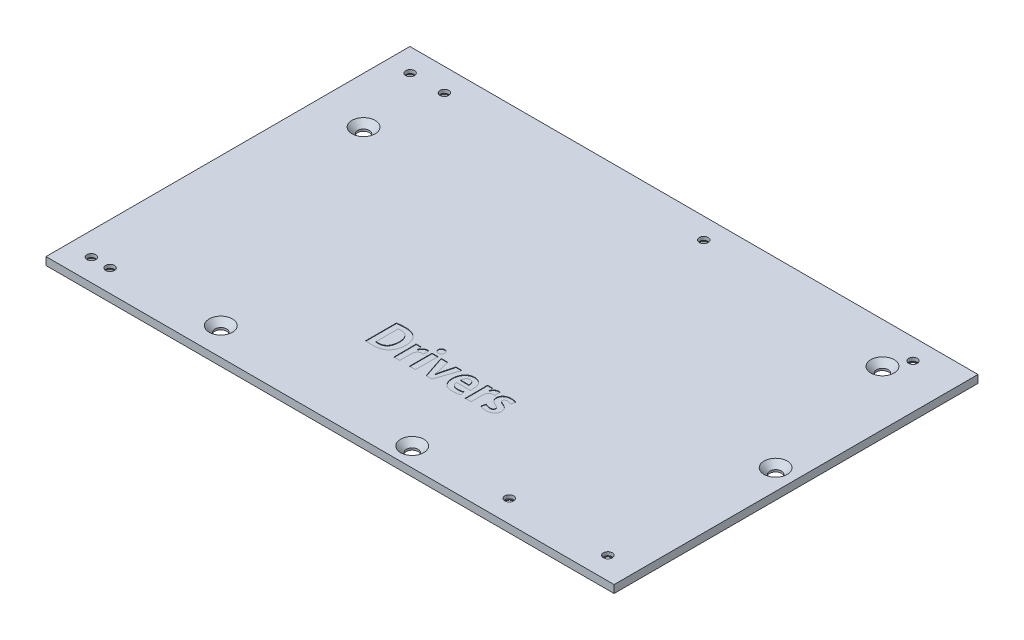
SolidWorks part; units mm, degrees
ref_plane "Alzado" through (0, 0, 0) normal (0, 0, 1) x (1, 0, 0)
ref_plane "Planta" through (0, 0, 0) normal (0, 1, 0) x (1, 0, 0)
ref_plane "Vista lateral" through (0, 0, 0) normal (1, 0, 0) x (0, 0, -1)
sketch "Sketch1" plane through (0, 0, 0) normal (0, 1, 0) x (1, 0, 0)
  line L1 (-104.4575, -65.119) -> (104.4575, -65.119)
  line L2 (-104.4575, -65.119) -> (-104.4575, 65.119)
  line L3 (-104.4575, 65.119) -> (104.4575, 65.119)
  line L4 (104.4575, -65.119) -> (104.4575, 65.119)
  line L5 (-104.4575, -65.119) -> (104.4575, 65.119) construction
  line L6 (-104.4575, 65.119) -> (104.4575, -65.119) construction
  circle A0 centre (-100.5175, 61.251) radius 1.5
  circle A1 centre (-87.3095, 61.251) radius 1.5
  circle A2 centre (92.3925, 62.141) radius 1.5
  circle A3 centre (11.7475, 62.141) radius 1.5
  circle A4 centre (60.4925, -61.559) radius 1.5
  circle A5 centre (98.4925, -61.559) radius 1.5
  circle A6 centre (-93.3165, -61.559) radius 1.5
  circle A7 centre (-100.5175, -61.559) radius 1.5
  point P0 (0, 0)
  dimension "D3" = 3.94
  dimension "D5" = 3
  dimension "D1" = 130.238
  dimension "D2" = 208.915
  dimension "D4" = 3.56
  dimension "D6" = 199.01
  dimension "D7" = 123.7
  dimension "D8" = 6.1
  dimension "D9" = 122.81
  dimension "D10" = 192.91
  dimension "D11" = 38
  dimension "D12" = 153.809
  dimension "D13" = 80.645
  dimension "D14" = 13.208
sketch "Sketch2" plane through (0, 0, 0) normal (0, 1, 0) x (1, 0, 0)
  line L16 (-109.4575, -70.119) -> (109.4575, -70.119)
  line L17 (-109.4575, 70.119) -> (-109.4575, -70.119)
  line L18 (109.4575, 70.119) -> (-109.4575, 70.119)
  line L19 (109.4575, -70.119) -> (109.4575, 70.119)
  line L20 (-109.4575, -70.119) -> (109.4575, -70.119)
  line L21 (-109.4575, 70.119) -> (-109.4575, -70.119)
  line L22 (109.4575, 70.119) -> (-109.4575, 70.119)
  line L23 (109.4575, -70.119) -> (109.4575, 70.119)
  circle A0 centre (-100.5175, -61.559) radius 1.5 construction
  circle A1 centre (-93.3165, -61.559) radius 1.5 construction
  circle A2 centre (98.4925, -61.559) radius 1.5 construction
  circle A3 centre (60.4925, -61.559) radius 1.5 construction
  circle A4 centre (92.3925, 62.141) radius 1.5 construction
  circle A5 centre (11.7475, 62.141) radius 1.5 construction
  circle A6 centre (-100.5175, 61.251) radius 1.5 construction
  circle A7 centre (-87.3095, 61.251) radius 1.5 construction
  circle A8 centre (-87.3095, 61.251) radius 1.5
  circle A9 centre (-100.5175, 61.251) radius 1.5
  circle A10 centre (11.7475, 62.141) radius 1.5
  circle A11 centre (92.3925, 62.141) radius 1.5
  circle A12 centre (60.4925, -61.559) radius 1.5
  circle A13 centre (98.4925, -61.559) radius 1.5
  circle A14 centre (-93.3165, -61.559) radius 1.5
  circle A15 centre (-100.5175, -61.559) radius 1.5
  dimension "D1" = 5
extrude "Boss-Extrude1" add sketch "Sketch2" along normal blind 3
sketch "Sketch3" plane through (0, 3, 0) normal (0, 1, 0) x (1, 0, 0)
  line L0 (-20.9409, -36.6466) -> (64.3186, -36.6466) construction
  line L1 (-104.4575, 65.119) -> (104.4575, -65.119) construction
  text T0 "Drivers" font "Adobe Gothic Std B" height 12
extrude "Cut-Extrude2" cut sketch "Sketch3" against normal blind 0.2
sketch "Sketch4" plane through (0, 3, 0) normal (0, 1, 0) x (1, 0, 0)
  line L4 (-104.4575, -65.119) -> (104.4575, -65.119)
  line L5 (104.4575, -65.119) -> (104.4575, 65.119)
  line L6 (104.4575, 65.119) -> (-104.4575, 65.119)
  line L7 (-104.4575, 65.119) -> (-104.4575, -65.119)
  line L8 (-104.4575, -65.119) -> (104.4575, -65.119)
  line L9 (104.4575, -65.119) -> (104.4575, 65.119)
  line L10 (104.4575, 65.119) -> (-104.4575, 65.119)
  line L11 (-104.4575, 65.119) -> (-104.4575, -65.119)
  circle A1 centre (60.4925, -61.559) radius 1.5
  circle A2 centre (60.4925, -61.559) radius 1.5
  circle A3 centre (11.7475, 62.141) radius 1.5
  circle A4 centre (11.7475, 62.141) radius 1.5
  circle A5 centre (92.3925, 62.141) radius 1.5
  circle A6 centre (92.3925, 62.141) radius 1.5
  circle A7 centre (-87.3095, 61.251) radius 1.5
  circle A8 centre (-87.3095, 61.251) radius 1.5
  circle A9 centre (-100.5175, 61.251) radius 1.5
  circle A10 centre (-100.5175, 61.251) radius 1.5
  circle A11 centre (-100.5175, -61.559) radius 1.5
  circle A12 centre (-100.5175, -61.559) radius 1.5
  circle A13 centre (-93.3165, -61.559) radius 1.5
  circle A14 centre (-93.3165, -61.559) radius 1.5
  circle A15 centre (98.4925, -61.559) radius 1.5
  circle A16 centre (98.4925, -61.559) radius 1.5
  dimension "D1" = 0
  dimension "D2" = 0
  dimension "D3" = 0
  dimension "D4" = 0
  dimension "D5" = 0
  dimension "D6" = 0
  dimension "D7" = 0
  dimension "D8" = 0
  dimension "D9" = 0
extrude "Boss-Extrude2" [suppressed] add sketch "Sketch4" along normal blind 2
sketch "Sketch5" plane through (0, 0, 0) normal (0, -1, 0) x (1, 0, 0)
  line L0 (-62.546, 67.4022) -> (124.1921, -83.3589) construction
  line L1 (-109.4575, -70.119) -> (-109.4575, 70.119) construction
  line L2 (109.4575, 70.119) -> (109.4575, -70.119) construction
  line L3 (109.4575, -70.119) -> (-109.4575, -70.119) construction
  line L4 (-109.4575, 70.119) -> (109.4575, 70.119) construction
  line L5 (0.2472, 42.6075) -> (-61.066, -8.7802) construction
  line L6 (-109.4575, -49.3381) -> (33.0725, 70.119) construction
  circle A0 centre (-52.7309, 59.478) radius 2.4699
  circle A1 centre (-91.4772, -34.2685) radius 2.1023
  circle A2 centre (88.3441, -54.4174) radius 2.6744
  circle A3 centre (24.3004, 62.767) radius 2.289
  circle A4 centre (101.6013, 0) radius 2.0628
  point P18 (-30.4094, 16.9136)
  dimension "D1" = 46.9115
  dimension "D2" = 14.7346
  dimension "D3" = 13.2399
  dimension "D4" = 2.7168
  dimension "D5" = 61.3388
  dimension "D6" = 48.3915
  dimension "D7" = 27.5115
  dimension "D8" = 109.7047
hole_wizard "CSK for M4 Hex Socket Countersunk Cap Screw1" positions "Sketch6" profile "Sketch7" countersink size "M4" standard "ISO" end condition through all
sketch "Sketch6" plane through (0, 3, 0) normal (0, 1, 0) x (1, 0, 0)
  point P0 (-52.7309, -59.478)
  point P3 (24.3004, -62.767)
  point P6 (-91.4772, 34.2685)
  point P9 (88.3441, 54.4174)
  point P12 (101.6013, 0)
sketch "Sketch7" plane through (-52.7309, 3, 59.478) normal (1, 0, 0) x (0, 0, 1)
  line L0 (0, 0) -> (0, 3)
  line L1 (0, 3) -> (2.25, 3)
  line L2 (2.25, 3) -> (2.25, 2.23)
  line L3 (2.25, 2.23) -> (4.48, 0)
  line L5 (4.48, 0) -> (0, 0)
  line L6 (-2.25, 2.23) -> (-4.48, 0) construction
  line L11 (0, -6.35) -> (0, 107.95) construction
  dimension "Thru Hole Dia." = 4.5
  dimension "Thru Hole Depth" = 3
  dimension "Near C'Sink Dia." = 8.96
  dimension "Near C'Sink Angle" = 90
sketch "Sketch8" [suppressed] plane through (0, 3, 0) normal (0, 1, 0) x (1, 0, 0)
  circle A0 centre (-91.4772, 34.2685) radius 1
  circle A1 centre (-52.7309, -59.478) radius 1
  circle A2 centre (24.3004, -62.767) radius 1
  circle A3 centre (88.3441, 54.4174) radius 1
  circle A4 centre (101.6013, 0) radius 1
  dimension "D1" = 2
extrude "Cut-Extrude3" [suppressed] cut sketch "Sketch8" against normal through all
sketch "Sketch9" plane through (0, 3, 0) normal (0, 1, 0) x (1, 0, 0)
  line L1 (-86.8238, 49.4582) -> (96.769, 49.4582)
  line L2 (-86.8238, 49.4582) -> (-86.8238, -54.3116)
  line L3 (-86.8238, -54.3116) -> (96.769, -54.3116)
  line L4 (96.769, 49.4582) -> (96.769, -54.3116)
  line L5 (-86.8238, 49.4582) -> (96.769, -54.3116) construction
  line L6 (-86.8238, -54.3116) -> (96.769, 49.4582) construction
  point P4 (4.9726, -2.4267)
extrude "Cut-Extrude4" [suppressed] cut sketch "Sketch9" against normal through all
sketch "Sketch14" plane through (0, 3, 0) normal (0, 1, 0) x (1, 0, 0)
  circle A0 centre (-100.5175, 61.251) radius 3.5013
  circle A1 centre (-87.3095, 61.251) radius 3.5013
  circle A2 centre (11.7475, 62.141) radius 3.5013
  circle A3 centre (92.3925, 62.141) radius 3.5013
  circle A4 centre (98.4925, -61.559) radius 3.5013
  circle A5 centre (60.4925, -61.559) radius 3.5013
  circle A6 centre (-93.3165, -61.559) radius 3.5013
  circle A7 centre (-100.5175, -61.559) radius 3.5013
  dimension "D1" = 7.0025
extrude "Boss-Extrude3" [suppressed] add sketch "Sketch14" along normal blind 3
fillet "Fillet1" [suppressed] radius 5
hole_wizard "CSK for M3 Hex Socket Countersunk Cap Screw1" positions "Sketch11" profile "Sketch12" countersink size "M3" standard "ISO" end condition through all
sketch "Sketch11" plane through (0, 0, 0) normal (0, -1, 0) x (-1, 0, 0)
  point P0 (-92.3925, 62.141)
  point P3 (-11.7475, 62.141)
  point P6 (87.3095, 61.251)
  point P9 (100.5175, 61.251)
  point P12 (93.3165, -61.559)
  point P15 (100.5175, -61.559)
  point P18 (-60.4925, -61.559)
  point P21 (-98.4925, -61.559)
sketch "Sketch12" plane through (92.3925, 0, -62.141) normal (1, 0, 0) x (0, 0, -1)
  line L0 (0, 0) -> (0, 3)
  line L1 (0, 3) -> (1.7, 3)
  line L2 (1.7, 3) -> (1.7, 1.66)
  line L3 (1.7, 1.66) -> (3.36, 0)
  line L5 (3.36, 0) -> (0, 0)
  line L6 (-1.7, 1.66) -> (-3.36, 0) construction
  line L11 (0, -6.35) -> (0, 107.95) construction
  dimension "Thru Hole Dia." = 3.4
  dimension "Thru Hole Depth" = 3
  dimension "Near C'Sink Dia." = 6.72
  dimension "Near C'Sink Angle" = 90
fillet "Fillet2" [suppressed] radius 3
